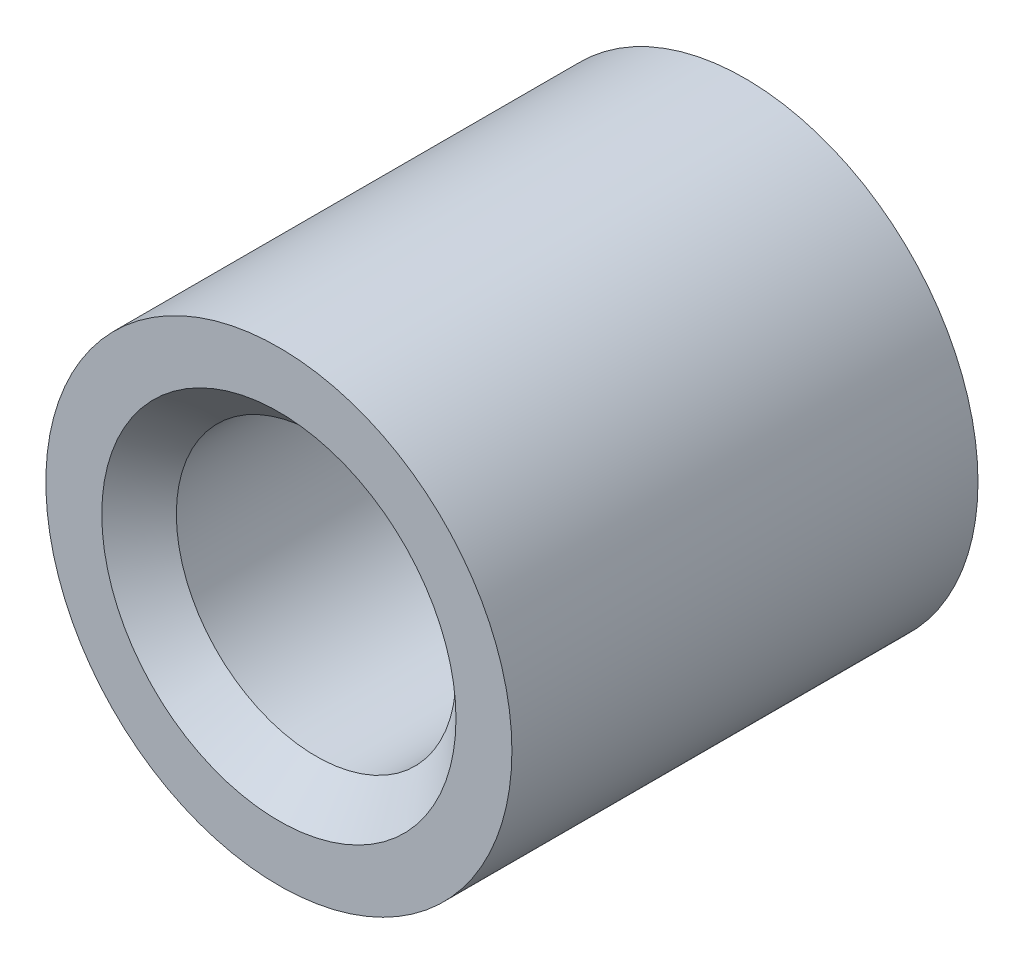
SolidWorks part; units mm, degrees
ref_plane "Front Plane" through (0, 0, 0) normal (0, 0, 1) x (1, 0, 0)
ref_plane "Top Plane" through (0, 0, 0) normal (0, 1, 0) x (1, 0, 0)
ref_plane "Right Plane" through (0, 0, 0) normal (1, 0, 0) x (0, 0, -1)
sketch "Sketch2" plane through (0, 0, 0) normal (0, 0, 1) x (1, 0, 0)
  circle A0 centre (0, 0) radius 4.7625
  circle A1 centre (0, 0) radius 7.9375
  dimension "D1" = 15.875
  dimension "D2" = 9.525
extrude "Boss-Extrude1" add sketch "Sketch2" along normal blind 15.875
chamfer "Chamfer1" distance 1.27 angle 45 2 edges at (4.7625, 0, 0) (4.7625, 0, 15.875)
